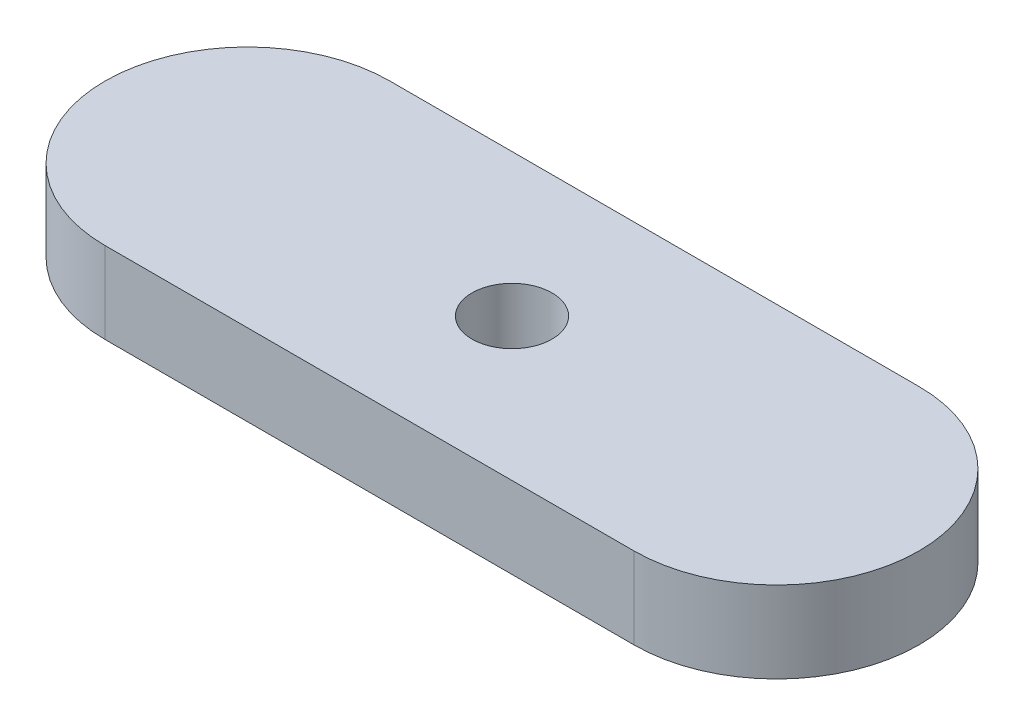
SolidWorks part; units mm, degrees
ref_plane "Front Plane" through (0, 0, 0) normal (0, 0, 1) x (1, 0, 0)
ref_plane "Top Plane" through (0, 0, 0) normal (0, 1, 0) x (1, 0, 0)
ref_plane "Right Plane" through (0, 0, 0) normal (1, 0, 0) x (0, 0, -1)
sketch "Sketch1" plane through (0, 0, 0) normal (0, 1, 0) x (1, 0, 0)
  line L0 (0, 0) -> (16.51, 0) construction
  line L1 (0, 4.445) -> (16.51, 4.445)
  line L2 (0, -4.445) -> (16.51, -4.445)
  arc A0 (0, 4.445) -> (0, -4.445) centre (0, 0) ccw
  arc A1 (16.51, -4.445) -> (16.51, 4.445) centre (16.51, 0) ccw
  circle A2 centre (8.255, 0) radius 1.25
  point P3 (8.255, 0)
  dimension "D2" = 16.51
  dimension "D3" = 2.5
  dimension "D1" = 8.89
extrude "Boss-Extrude1" add sketch "Sketch1" along normal blind 2.54
